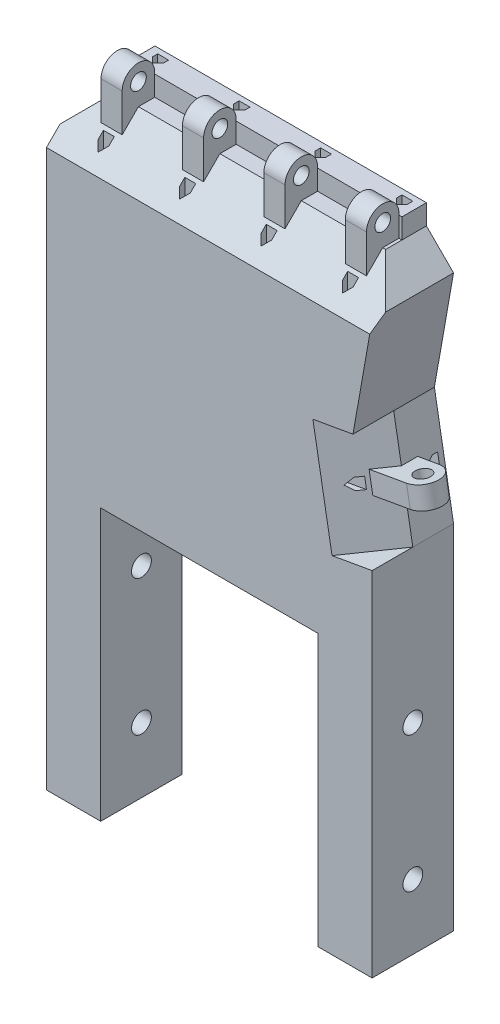
SolidWorks part; units mm, degrees
material "Custom Plastic"
ref_plane "Front Plane" through (0, 0, 0) normal (0, 0, 1) x (1, 0, 0)
ref_plane "Top Plane" through (0, 0, 0) normal (0, 1, 0) x (1, 0, 0)
ref_plane "Right Plane" through (0, 0, 0) normal (1, 0, 0) x (0, 0, -1)
sketch "Sketch1" plane through (0, 0, 0) normal (0, 0, 1) x (1, 0, 0)
  line L1 (-30, -30) -> (30, -30)
  line L2 (-30, -30) -> (-30, 30)
  line L3 (-30, 30) -> (30, 30)
  line L4 (30, -30) -> (30, 30)
  line L5 (-30, -30) -> (30, 30) construction
  line L6 (-30, 30) -> (30, -30) construction
  point P0 (0, 0)
  dimension "D1" = 60
  dimension "D2" = 60
extrude "Boss-Extrude1" add sketch "Sketch1" along normal mid plane 15
sketch "Sketch2" plane through (0, 0, 0) normal (0, 0, 1) x (1, 0, 0)
  line L0 (-30, 25) -> (-25, 30)
  line L1 (-30, 30) -> (-30, -30) construction
  line L2 (30, 30) -> (-30, 30) construction
  line L3 (-25, 30) -> (25, 30)
  line L4 (25, 30) -> (30, 25)
  line L5 (30, -30) -> (30, 30) construction
  line L10 (-30, -30) -> (30, -30) construction
  line L11 (14.5979, -30) -> (-15, -30)
  line L13 (-30, -15) -> (-30, 25)
  line L15 (-30, -15) -> (-30, -30)
  line L16 (-30, -30) -> (-15, -30)
  line L17 (14.5979, -30) -> (30, -30)
  line L18 (30, -30) -> (30, -15)
  line L19 (30, 25) -> (26.4735, 5)
  line L20 (26.4735, 5) -> (30, -15)
  dimension "D1" = 5
  dimension "D2" = 5
  dimension "D3" = 5
  dimension "D4" = 5
  dimension "D5" = 170
  dimension "D6" = 20
  dimension "D7" = 15
extrude "Cut-Extrude6" cut sketch "Sketch2" against normal through all both and the other way through all flip side to cut
ref_plane "Plane1" through (29.5, 0, 0) normal (1, 0, 0) x (0, 0, -1)
sketch "Sketch9" plane through (0, 0, 0) normal (1, 0, 0) x (0, 0, -1)
  line L0 (-7.5, 30) -> (0, 30)
  line L1 (7.5, 30) -> (-7.5, 30) construction
  line L7 (0, 30) -> (-7.5, 22.5)
  line L8 (-7.5, 5) -> (-7.5, 25) construction
  line L9 (-7.5, 22.5) -> (-7.5, 30)
  dimension "D1" = 45
  dimension "D2" = 7.5
extrude "Cut-Extrude7" cut sketch "Sketch9" against normal through all both and the other way through all
sketch "Sketch25" plane through (0, -30, 0) normal (0, -1, 0) x (1, 0, 0)
  line L0 (-30, 7.5) -> (30, 7.5) construction
  line L1 (-30, -7.5) -> (-20, -7.5)
  line L2 (-30, -7.5) -> (-30, 7.5)
  line L3 (-30, 7.5) -> (-20, 7.5)
  line L4 (-20, -7.5) -> (-20, 7.5)
  line L5 (-30, -7.5) -> (-20, 7.5) construction
  line L6 (-30, 7.5) -> (-20, -7.5) construction
  line L8 (0, -8.25) -> (0, 8.25) construction
  line L9 (30, 7.5) -> (20, 7.5)
  line L10 (20, -7.5) -> (20, 7.5)
  line L11 (30, -7.5) -> (20, -7.5)
  line L12 (30, -7.5) -> (30, 7.5)
  point P0 (-25, 0)
  dimension "D1" = 15
  dimension "D2" = 10
  dimension "D3" = 20
extrude "Boss-Extrude5" add sketch "Sketch25" along normal blind 50
sketch "Sketch26" plane through (-20, 0, 0) normal (1, 0, 0) x (0, 0, -1)
  line L5 (7.5, -80) -> (-7.5, -80) construction
  circle A0 centre (0, -68) radius 1.825
  circle A1 centre (0, -43) radius 1.825
  dimension "D1" = 3.65
  dimension "D2" = 3.65
  dimension "D3" = 12
  dimension "D4" = 25
extrude "Cut-Extrude22" cut sketch "Sketch26" against normal through all both and the other way through all
ref_plane "Plane4" through (-22.5, 0, 0) normal (-1, 0, 0) x (0, 0, 1)
ref_plane "Plane5" through (1.7065, -9.678, 0) normal (-0.1736, 0.9848, 0) x (0.9848, 0.1736, 0)
sketch "Sketch31" plane through (1.7065, -9.678, 0) normal (-0.1736, 0.9848, 0) x (0.9848, 0.1736, 0)
  line L0 (26.9395, -7.5) -> (19.4395, -7.5)
  line L1 (19.4395, -7.5) -> (26.9395, 0)
  line L2 (26.9395, 0) -> (26.9395, -7.5)
  line L7 (26.9395, 7.5) -> (26.9395, -7.5) construction
  line L8 (26.9395, -7.5) -> (33.0172, -7.5) construction
  dimension "D1" = 45
  dimension "D2" = 7.5
extrude "Cut-Extrude25" cut sketch "Sketch31" against normal up to vertex (10.1543 mm away) and the other way up to vertex (10.1543 mm away)
sketch "Sketch36" plane through (0, -30, 0) normal (0, -1, 0) x (1, 0, 0)
  line L0 (0, 6.5) -> (-2, 4.5)
  line L1 (-2, 4.5) -> (-2, 2.5)
  line L2 (-2, 2.5) -> (2, 2.5)
  line L3 (2, 2.5) -> (2, 4.5)
  line L4 (2, 4.5) -> (0, 6.5)
  line L5 (-20, 7.5) -> (20, 7.5) construction
  point P8 (0, 7.5)
  dimension "D1" = 2
  dimension "D2" = 135
  dimension "D3" = 2
  dimension "D4" = 135
  dimension "D5" = 4
  dimension "D6" = 1
extrude "Cut-Extrude29" cut sketch "Sketch36" against normal up to surface (30 mm away)
pattern_linear "LPattern3" count 2 spacing 9 along (0, 0, -1) of "Cut-Extrude29"
sketch "Sketch41" plane through (0, 30, 0) normal (0, 1, 0) x (1, 0, 0)
  line L0 (-23.5, 6.5) -> (-21.5, 6.5)
  line L1 (-21.5, 6.5) -> (-21.5, 5.5)
  line L2 (-21.5, 5.5) -> (-22.5, 4.5)
  line L3 (-22.5, 8.25) -> (-22.5, -8.25) construction
  line L4 (-22.5, 4.5) -> (-23.5, 5.5)
  line L5 (-23.5, 5.5) -> (-23.5, 6.5)
  line L6 (25, 7.5) -> (-25, 7.5) construction
  line L7 (-8.5, 5.5) -> (-8.5, 6.5)
  line L8 (-8.5, 6.5) -> (-6.5, 6.5)
  line L9 (-6.5, 6.5) -> (-6.5, 5.5)
  line L10 (-6.5, 5.5) -> (-7.5, 4.5)
  line L11 (-7.5, 4.5) -> (-8.5, 5.5)
  line L12 (6.5, 5.5) -> (6.5, 6.5)
  line L13 (6.5, 6.5) -> (8.5, 6.5)
  line L14 (8.5, 6.5) -> (8.5, 5.5)
  line L15 (8.5, 5.5) -> (7.5, 4.5)
  line L16 (7.5, 4.5) -> (6.5, 5.5)
  line L17 (21.5, 5.5) -> (21.5, 6.5)
  line L18 (21.5, 6.5) -> (23.5, 6.5)
  line L19 (23.5, 6.5) -> (23.5, 5.5)
  line L20 (23.5, 5.5) -> (22.5, 4.5)
  line L21 (22.5, 4.5) -> (21.5, 5.5)
  line L22 (-8.5, -4.5) -> (-8.5, -3.5)
  line L23 (-8.5, -3.5) -> (-6.5, -3.5)
  line L24 (-6.5, -3.5) -> (-6.5, -4.5)
  line L25 (-6.5, -4.5) -> (-7.5, -5.5)
  line L26 (-7.5, -5.5) -> (-8.5, -4.5)
  line L27 (6.5, -4.5) -> (6.5, -3.5)
  line L28 (6.5, -3.5) -> (8.5, -3.5)
  line L29 (8.5, -3.5) -> (8.5, -4.5)
  line L30 (8.5, -4.5) -> (7.5, -5.5)
  line L31 (7.5, -5.5) -> (6.5, -4.5)
  line L32 (21.5, -4.5) -> (21.5, -3.5)
  line L33 (21.5, -3.5) -> (23.5, -3.5)
  line L34 (23.5, -3.5) -> (23.5, -4.5)
  line L35 (23.5, -4.5) -> (22.5, -5.5)
  line L36 (22.5, -5.5) -> (21.5, -4.5)
  line L37 (-23.5, -4.5) -> (-23.5, -3.5)
  line L38 (-23.5, -3.5) -> (-21.5, -3.5)
  line L39 (-21.5, -3.5) -> (-21.5, -4.5)
  line L40 (-21.5, -4.5) -> (-22.5, -5.5)
  line L41 (-22.5, -5.5) -> (-23.5, -4.5)
  dimension "D1" = 1
  dimension "D2" = 1
  dimension "D3" = 135
  dimension "D4" = 2
  dimension "D5" = 1
  dimension "D8" = 8
  dimension "D6" = 4
  dimension "D7" = 2
extrude "Cut-Extrude32" cut sketch "Sketch41" against normal blind 7
sketch "Sketch47" plane through (0, 30, 0) normal (0, 1, 0) x (1, 0, 0)
  line L0 (-25, 0) -> (25, 0) construction
  line L1 (-24.45, -3) -> (-20.55, -3)
  line L2 (-24.45, -3) -> (-24.45, 3)
  line L3 (-24.45, 3) -> (-20.55, 3)
  line L4 (-20.55, -3) -> (-20.55, 3)
  line L5 (-24.45, -3) -> (-20.55, 3) construction
  line L6 (-24.45, 3) -> (-20.55, -3) construction
  line L7 (-22.5, 8.25) -> (-22.5, -8.25) construction
  line L8 (-9.45, -3) -> (-9.45, 3)
  line L9 (-9.45, -3) -> (-5.55, -3)
  line L10 (-5.55, -3) -> (-5.55, 3)
  line L11 (-9.45, 3) -> (-5.55, 3)
  line L12 (-9.45, -3) -> (-5.55, 3) construction
  line L13 (-9.45, 3) -> (-5.55, -3) construction
  line L14 (5.55, -3) -> (5.55, 3)
  line L15 (5.55, -3) -> (9.45, -3)
  line L16 (9.45, -3) -> (9.45, 3)
  line L17 (5.55, 3) -> (9.45, 3)
  line L18 (5.55, -3) -> (9.45, 3) construction
  line L19 (5.55, 3) -> (9.45, -3) construction
  line L20 (20.55, -3) -> (20.55, 3)
  line L21 (20.55, -3) -> (24.45, -3)
  line L22 (24.45, -3) -> (24.45, 3)
  line L23 (20.55, 3) -> (24.45, 3)
  line L24 (20.55, -3) -> (24.45, 3) construction
  line L25 (20.55, 3) -> (24.45, -3) construction
  point P0 (-22.5, 0)
  point P11 (-7.5, 0)
  point P16 (7.5, 0)
  point P21 (22.5, 0)
  dimension "D1" = 3.9
  dimension "D2" = 6
  dimension "D3" = 4
extrude "Boss-Extrude6" add sketch "Sketch47" along normal mid plane 8
sketch "Sketch59" plane through (0, 30, 0) normal (0, 1, 0) x (1, 0, 0)
  line L0 (-25, 7.5) -> (-25, 3)
  line L1 (-25, 7.5) -> (-25, 0) construction
  line L2 (-25, 3) -> (25, 3)
  line L3 (25, 7.5) -> (25, 0) construction
  line L4 (25, 3) -> (25, 7.5)
  line L5 (25, 7.5) -> (-25, 7.5)
  line L6 (-20.55, 3) -> (-24.45, 3) construction
extrude "Boss-Extrude8" add sketch "Sketch59" along normal blind 3.7
sketch "Sketch49" plane through (0, 34, 0) normal (0, 1, 0) x (1, 0, 0)
  line L0 (-22.5, 8.25) -> (-22.5, -8.25) construction
  line L1 (-24.45, 0) -> (-20.55, 0)
  line L2 (-24.45, 0) -> (-24.45, 3)
  line L3 (-24.45, 3) -> (-20.55, 3)
  line L4 (-20.55, 0) -> (-20.55, 3)
  line L5 (-24.45, 0) -> (-20.55, 3) construction
  line L6 (-24.45, 3) -> (-20.55, 0) construction
  line L7 (-24.45, 3) -> (-24.45, 0) construction
  point P0 (-22.5, 1.5)
revolve "Revolve2" add sketch "Sketch49" angle 180 about L1
pattern_linear "LPattern7" count 4 spacing 15 along (1, 0, 0) of "Revolve2"
sketch "Sketch50" plane through (-24.45, 0, 0) normal (-1, 0, 0) x (0, 0, 1)
  line L0 (-3, 34) -> (3, 34) construction
  circle A0 centre (0, 34) radius 1.45
  dimension "D1" = 2.9
extrude "Cut-Extrude38" cut sketch "Sketch50" against normal through all both and the other way through all
sketch "Sketch51" plane through (26.5302, 4.678, 0) normal (0.9848, 0.1736, 0) x (0, 0, -1)
  line L0 (3.8203, -9.8273) -> (-3.8203, -9.8273) construction
  line L1 (3, -11.7773) -> (-3, -11.7773)
  line L2 (3, -11.7773) -> (3, -7.8773)
  line L3 (3, -7.8773) -> (-3, -7.8773)
  line L4 (-3, -11.7773) -> (-3, -7.8773)
  line L5 (3, -11.7773) -> (-3, -7.8773) construction
  line L6 (3, -7.8773) -> (-3, -11.7773) construction
  line L8 (0, -19.9816) -> (0, 0.327) construction
  point P0 (0, -9.8273)
  dimension "D1" = 6
  dimension "D2" = 3.9
extrude "Boss-Extrude7" add sketch "Sketch51" along normal mid plane 8
sketch "Sketch52" plane through (30.4695, 5.3726, 0) normal (0.9848, 0.1736, 0) x (0, 0, -1)
  line L0 (3.8203, -9.8273) -> (-3.8203, -9.8273) construction
  line L1 (0, -11.7773) -> (3, -11.7773)
  line L2 (0, -11.7773) -> (0, -7.8773)
  line L3 (0, -7.8773) -> (3, -7.8773)
  line L4 (3, -11.7773) -> (3, -7.8773)
  line L5 (0, -11.7773) -> (3, -7.8773) construction
  line L6 (0, -7.8773) -> (3, -11.7773) construction
  point P0 (1.5, -9.8273)
revolve "Revolve4" add sketch "Sketch52" angle 180 about L2
sketch "Sketch53" plane through (1.3679, -7.7576, 0) normal (-0.1736, 0.9848, 0) x (0.9848, 0.1736, 0)
  line L0 (30.9395, 3) -> (30.9395, -3) construction
  arc A0 (30.9395, -3) -> (30.9395, 3) centre (30.9395, 0) ccw construction
  circle A1 centre (30.9395, 0) radius 1.45
  dimension "D1" = 2.9
extrude "Cut-Extrude39" cut sketch "Sketch53" against normal up to surface (3.9 mm away) up to face at (30.151, -6.6425, 0)
ref_plane "Plane3" through (-21.4721, 23.026, 0) normal (0.682, -0.7314, 0) x (0, 0, -1)
sketch "Sketch56" plane through (0, 23, 0) normal (0, 1, 0) x (1, 0, 0)
  line L0 (-22.5, -5.5) -> (-21.5, -4.5)
  line L1 (-21.5, -4.5) -> (-21.5, -3.5)
  line L2 (-21.5, -3.5) -> (-23.5, -3.5)
  line L3 (-23.5, -3.5) -> (-23.5, -4.5)
  line L4 (-23.5, -4.5) -> (-22.5, -5.5)
extrude "Cut-Extrude40" cut sketch "Sketch56" along direction (0.682, -0.7314, 0) on the side against the normal up to surface (23 mm away)
ref_plane "Plane6" through (-6.5879, 22.9748, 0) normal (-0.2756, 0.9613, 0) x (0, 0, -1)
sketch "Sketch57" plane through (0, 23, 0) normal (0, 1, 0) x (1, 0, 0)
  line L0 (-7.5, -5.5) -> (-8.5, -4.5)
  line L1 (-8.5, -4.5) -> (-8.5, -3.5)
  line L2 (-8.5, -3.5) -> (-6.5, -3.5)
  line L3 (-6.5, -3.5) -> (-6.5, -4.5)
  line L4 (-6.5, -4.5) -> (-7.5, -5.5)
extrude "Cut-Extrude41" cut sketch "Sketch57" along direction (-0.2756, 0.9613, 0) on the side against the normal up to surface (23.9269 mm away)
mirror "Mirror1" about plane through (0, 0, 0) normal (1, 0, 0) of "Cut-Extrude40", "Cut-Extrude41"
pattern_linear "LPattern8" count 2 spacing 10 along (0, 0, -1) of "Mirror1", "Cut-Extrude40", "Cut-Extrude41"
fillet "Fillet1" radius 1 16 edges at (21.5, 23, 4) (6.5, 23, 4) (-6.5, 23, 4) (-21.5, 23, 4) (-23.5, 23, -6) (-21.5, 23, -6) (-6.5, 23, -6) (-8.5, 23, -6) (6.5, 23, -6) (8.5, 23, -6) (21.5, 23, -6) (23.5, 23, -6) (23.5, 23, 4) (8.5, 23, 4) (-8.5, 23, 4) (-23.5, 23, 4)
sketch "Sketch58" plane through (26.5302, 4.678, 0) normal (0.9848, 0.1736, 0) x (0, 0, -1)
  line L0 (6.5, -10.8273) -> (6.5, -8.8273)
  line L1 (6.5, -8.8273) -> (5.5, -8.8273)
  line L2 (5.5, -8.8273) -> (4.5, -9.8273)
  line L3 (4.5, -9.8273) -> (5.5, -10.8273)
  line L4 (5.5, -10.8273) -> (6.5, -10.8273)
  line L6 (3.8203, -9.8273) -> (-3.8203, -9.8273) construction
  line L7 (7.5, -19.9816) -> (7.5, 0.327) construction
  line L8 (-4.5, -10.8273) -> (-3.5, -10.8273)
  line L9 (-3.5, -10.8273) -> (-3.5, -8.8273)
  line L10 (-3.5, -8.8273) -> (-4.5, -8.8273)
  line L11 (-4.5, -8.8273) -> (-5.5, -9.8273)
  line L12 (-5.5, -9.8273) -> (-4.5, -10.8273)
  dimension "D1" = 2
  dimension "D2" = 1
  dimension "D3" = 1
  dimension "D4" = 135
  dimension "D5" = 1
  dimension "D7" = 8
  dimension "D6" = 2
extrude "Cut-Extrude42" cut sketch "Sketch58" against normal blind 29
sketch "Sketch60" plane through (0, 33.7, 0) normal (0, 1, 0) x (1, 0, 0)
  line L0 (-23.5, 6.5) -> (-21.5, 6.5)
  line L1 (-21.5, 6.5) -> (-21.5, 5.5)
  line L2 (-21.5, 5.5) -> (-22.5, 4.5)
  line L3 (-22.5, 4.5) -> (-23.5, 5.5)
  line L4 (-23.5, 5.5) -> (-23.5, 6.5)
  line L5 (25, 7.5) -> (-25, 7.5) construction
  line L6 (-8.5, 5.5) -> (-8.5, 6.5)
  line L7 (-8.5, 6.5) -> (-6.5, 6.5)
  line L8 (-6.5, 6.5) -> (-6.5, 5.5)
  line L9 (-6.5, 5.5) -> (-7.5, 4.5)
  line L10 (-7.5, 4.5) -> (-8.5, 5.5)
  line L11 (6.5, 5.5) -> (6.5, 6.5)
  line L12 (6.5, 6.5) -> (8.5, 6.5)
  line L13 (8.5, 6.5) -> (8.5, 5.5)
  line L14 (8.5, 5.5) -> (7.5, 4.5)
  line L15 (7.5, 4.5) -> (6.5, 5.5)
  line L16 (21.5, 5.5) -> (21.5, 6.5)
  line L17 (21.5, 6.5) -> (23.5, 6.5)
  line L18 (23.5, 6.5) -> (23.5, 5.5)
  line L19 (23.5, 5.5) -> (22.5, 4.5)
  line L20 (22.5, 4.5) -> (21.5, 5.5)
  dimension "D1" = 2
  dimension "D2" = 1
  dimension "D3" = 135
  dimension "D4" = 1
  dimension "D5" = 1
  dimension "D6" = 4
extrude "Cut-Extrude44" cut sketch "Sketch60" against normal blind 3.75
